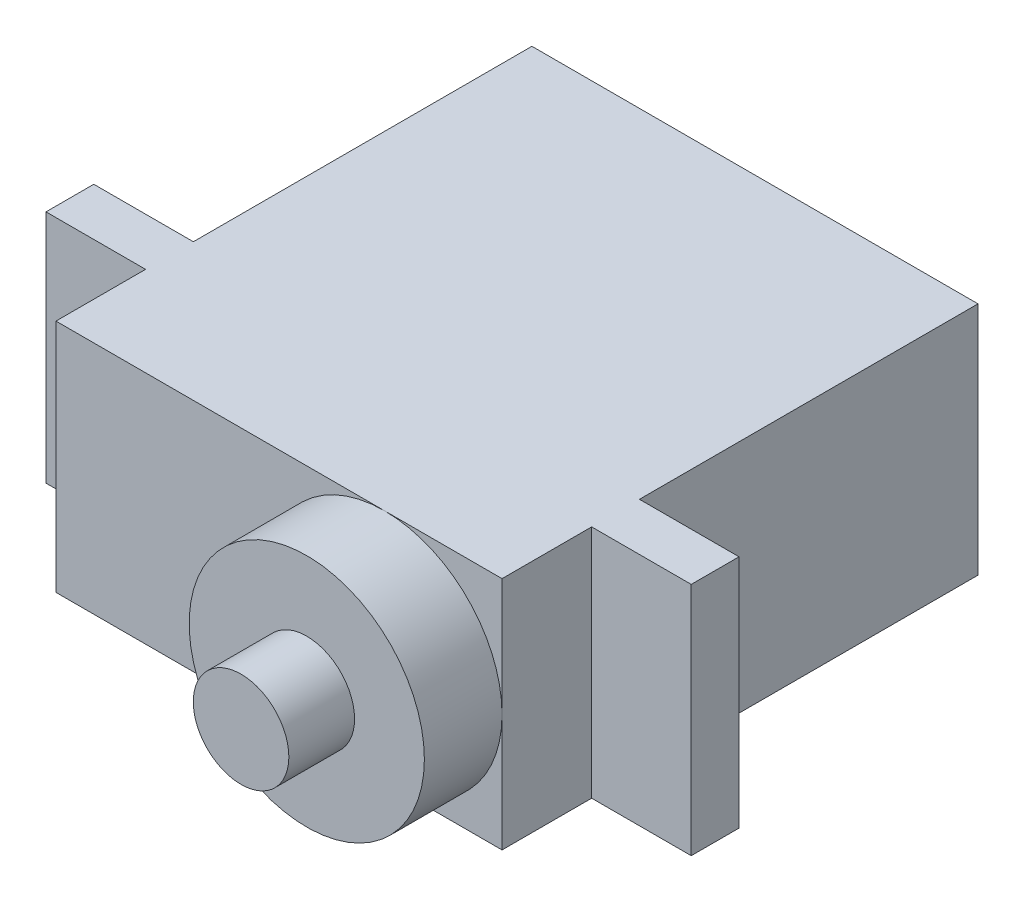
SolidWorks part; units mm, degrees
ref_plane "Alzado" through (0, 0, 0) normal (1, 0, 0) x (0, 1, 0)
ref_plane "Planta" through (0, 0, 0) normal (0, 0, 1) x (0, 1, 0)
ref_plane "Vista lateral" through (0, 0, 0) normal (0, 1, 0) x (-1, 0, 0)
sketch "Croquis1" plane through (0, 0, 0) normal (0, 0, 1) x (0, 1, 0)
  line L1 (5.9, -16.2) -> (-5.9, -16.2)
  line L2 (5.9, -16.2) -> (5.9, 16.2)
  line L3 (5.9, 16.2) -> (-5.9, 16.2)
  line L4 (-5.9, -16.2) -> (-5.9, 16.2)
  line L5 (5.9, -16.2) -> (-5.9, 16.2) construction
  line L6 (5.9, 16.2) -> (-5.9, -16.2) construction
  point P0 (0, 0)
extrude "Saliente-Extruir1" add sketch "Croquis1" along normal blind 2.4
sketch "Croquis2" plane through (0, 0, 2.4) normal (0, 0, 1) x (1, 0, 0)
  line L0 (16.2, 5.9) -> (-16.2, 5.9) construction
  line L1 (-11.2, 5.9) -> (11.2, 5.9)
  line L2 (-11.2, 5.9) -> (-11.2, -5.9)
  line L3 (-11.2, -5.9) -> (11.2, -5.9)
  line L4 (11.2, 5.9) -> (11.2, -5.9)
  line L5 (-16.2, -5.9) -> (16.2, -5.9) construction
extrude "Saliente-Extruir2" add sketch "Croquis2" along normal blind 4.5
sketch "Croquis3" plane through (0, 0, 6.9) normal (0, 0, 1) x (1, 0, 0)
  circle A1 centre (5.2948, -0.0052) radius 5.9052
extrude "Saliente-Extruir3" add sketch "Croquis3" along normal blind 3.9
sketch "Croquis4" plane through (0, 0, 10.8) normal (0, 0, 1) x (1, 0, 0)
  circle A0 centre (5.2948, -0.0052) radius 2.4
extrude "Saliente-Extruir4" add sketch "Croquis4" along normal blind 3.3
sketch "Croquis5" plane through (0, 0, 0) normal (0, 0, -1) x (1, 0, 0)
  line L0 (16.2, -5.9) -> (-16.2, -5.9) construction
  line L1 (-11.2, -5.9) -> (11.2, -5.9)
  line L2 (-11.2, -5.9) -> (-11.2, 5.9)
  line L3 (-11.2, 5.9) -> (11.2, 5.9)
  line L4 (11.2, -5.9) -> (11.2, 5.9)
  line L5 (-16.2, 5.9) -> (16.2, 5.9) construction
extrude "Saliente-Extruir5" add sketch "Croquis5" along normal blind 17
